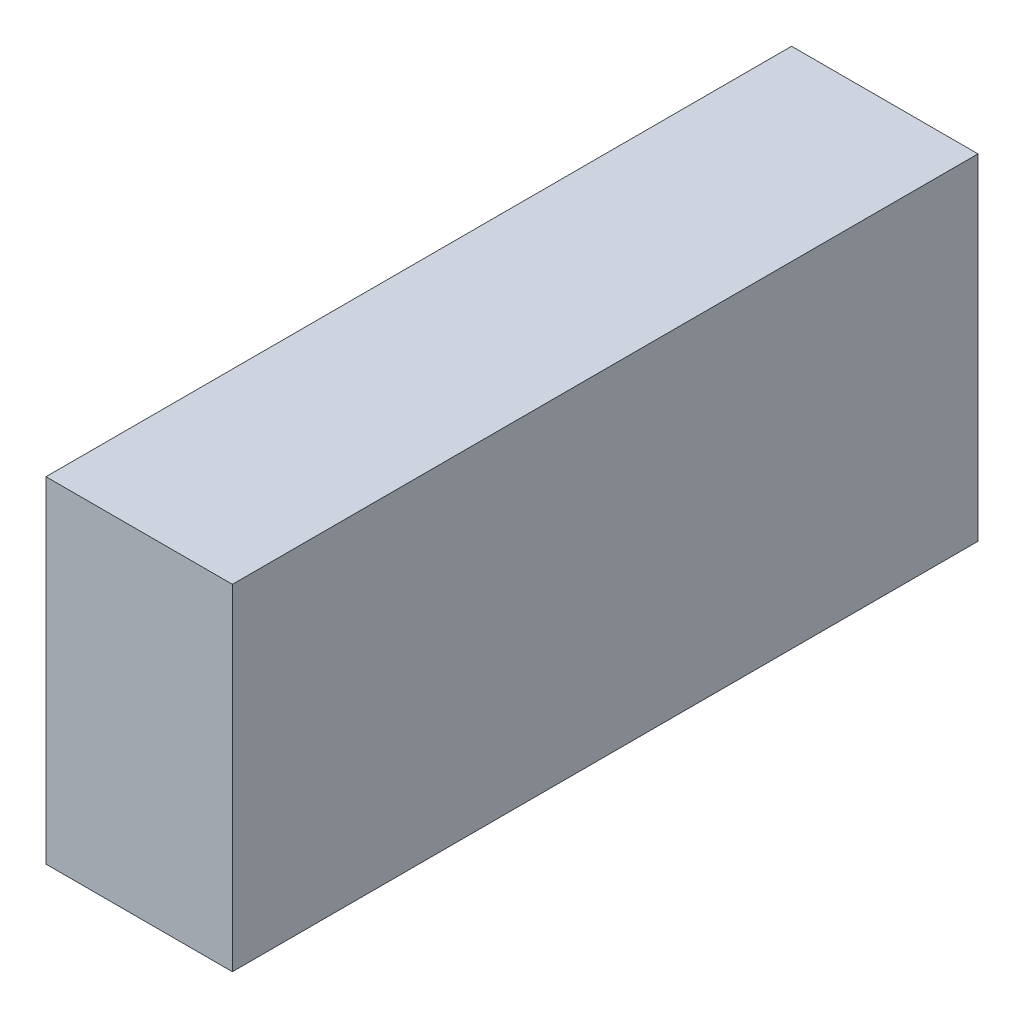
SolidWorks part; units mm, degrees
material "Porcelana cerâmica"
ref_plane "Plano frontal" through (0, 0, 0) normal (0, 0, 1) x (1, 0, 0)
ref_plane "Plano superior" through (0, 0, 0) normal (0, 1, 0) x (1, 0, 0)
ref_plane "Plano direito" through (0, 0, 0) normal (1, 0, 0) x (0, 0, -1)
sketch "Esboço1" plane through (0, 0, 0) normal (0, 0, 1) x (1, 0, 0)
  line L1 (0, 0) -> (50, 0)
  line L2 (0, 0) -> (0, 90)
  line L3 (0, 90) -> (50, 90)
  line L4 (50, 0) -> (50, 90)
  dimension "D1" = 90
  dimension "D2" = 50
extrude "Ressalto-extrusão1" add sketch "Esboço1" along normal blind 200
